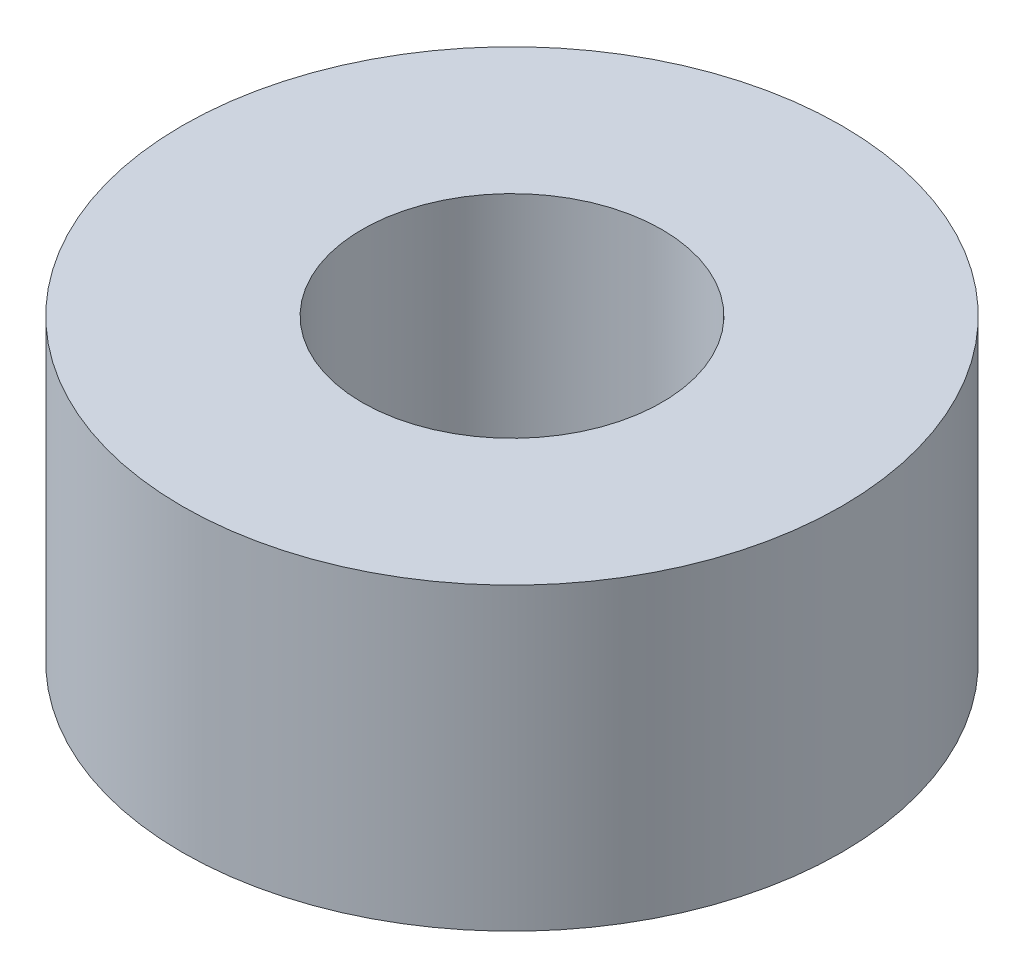
SolidWorks part; units mm, degrees
ref_plane "前视基准面" through (0, 0, 0) normal (0, 0, 1) x (1, 0, 0)
ref_plane "上视基准面" through (0, 0, 0) normal (0, 1, 0) x (1, 0, 0)
ref_plane "右视基准面" through (0, 0, 0) normal (1, 0, 0) x (0, 0, -1)
sketch "草图1" plane through (0, 0, 0) normal (0, 1, 0) x (1, 0, 0)
  circle A0 centre (0, 0) radius 2.5
  circle A1 centre (0, 0) radius 5.5
  dimension "D1" = 5
  dimension "D2" = 11
extrude "凸台-拉伸1" add sketch "草图1" along normal blind 5
